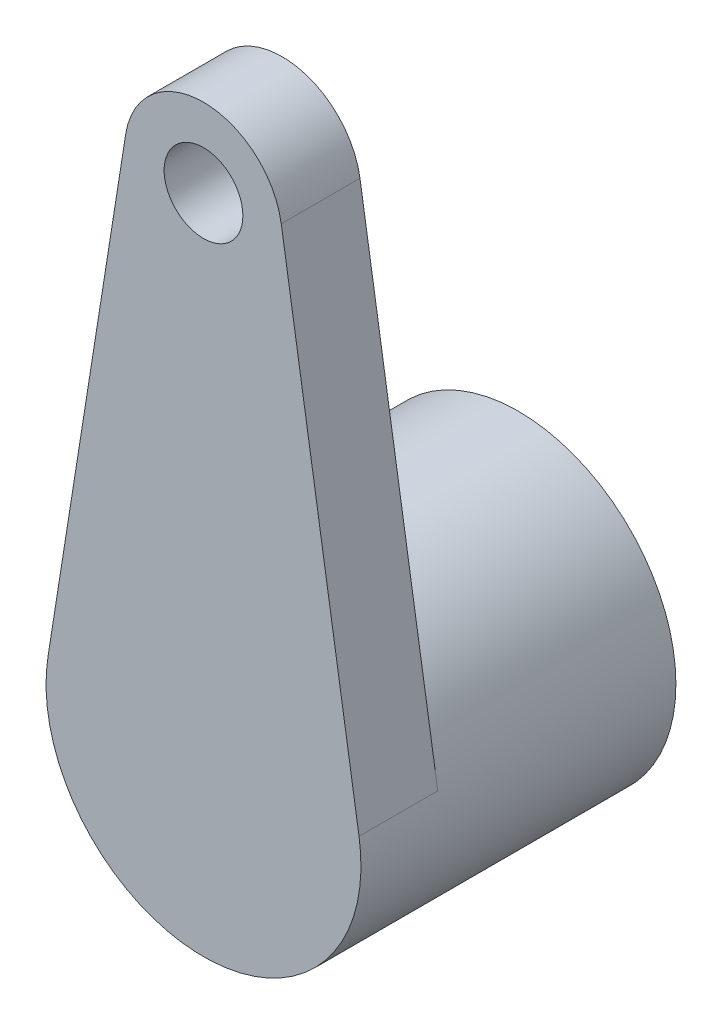
SolidWorks part; units mm, degrees
ref_plane "Front Plane" through (0, 0, 0) normal (0, 0, 1) x (1, 0, 0)
ref_plane "Top Plane" through (0, 0, 0) normal (0, 1, 0) x (1, 0, 0)
ref_plane "Right Plane" through (0, 0, 0) normal (1, 0, 0) x (0, 0, -1)
sketch "Sketch1" plane through (0, 0, 0) normal (0, 0, 1) x (1, 0, 0)
  circle A0 centre (14.6012, -1.5642) radius 1.5875
  circle A1 centre (14.6012, -1.5642) radius 3.175
extrude "Boss-Extrude1" add sketch "Sketch1" along normal blind 4.7625
sketch "Sketch2" plane through (0, 0, 4.7625) normal (0, 0, 1) x (1, 0, 0)
  line L0 (11.4652, -1.0681) -> (13.0332, 8.8438)
  line L1 (17.7372, -1.0681) -> (16.1692, 8.8438)
  arc A0 (11.4652, -1.0681) -> (17.7372, -1.0681) centre (14.6012, -1.5642) ccw
  circle A1 centre (14.6012, 8.5958) radius 0.7937
  arc A2 (16.1692, 8.8438) -> (13.0332, 8.8438) centre (14.6012, 8.5958) ccw
extrude "Boss-Extrude2" add sketch "Sketch2" along normal blind 1.5875
